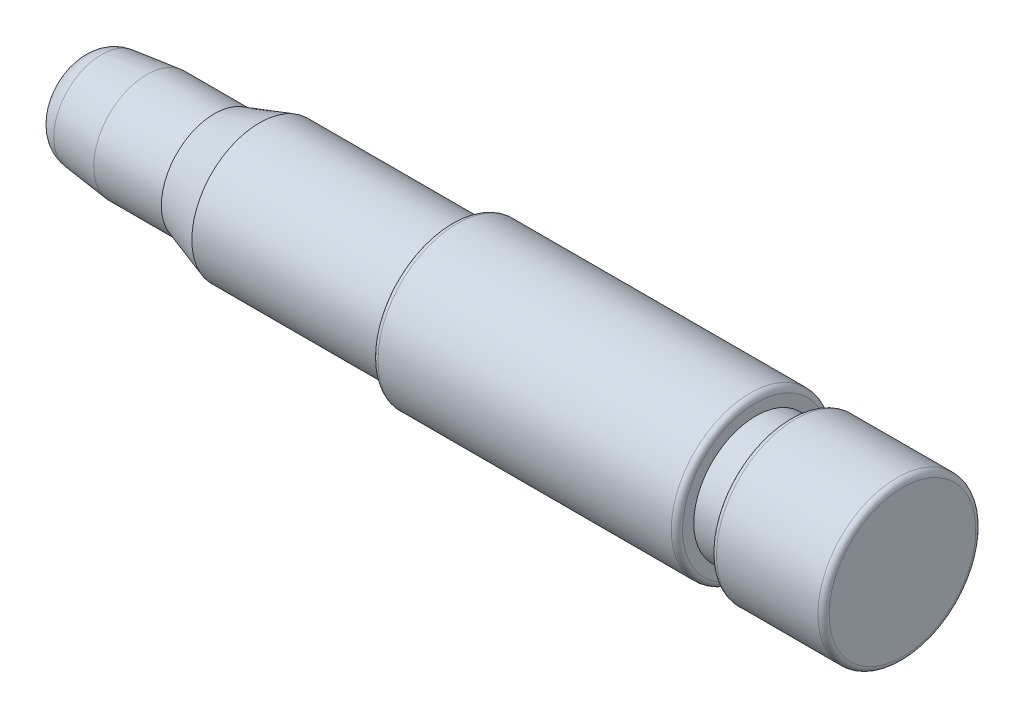
SolidWorks part; units mm, degrees
ref_plane "Plano frontal" through (0, 0, 0) normal (0, 0, 1) x (1, 0, 0)
ref_plane "Plano superior" through (0, 0, 0) normal (0, 1, 0) x (1, 0, 0)
ref_plane "Plano direito" through (0, 0, 0) normal (1, 0, 0) x (0, 0, -1)
sketch "Esboço1" plane through (0, 0, 0) normal (0, 0, 1) x (1, 0, 0)
  line L0 (0, 0) -> (73, 0)
  line L1 (73, 0) -> (73, 7)
  line L2 (73, 7) -> (63, 7)
  line L3 (63, 7) -> (63, 5.5)
  line L4 (63, 5.5) -> (60, 5.5)
  line L5 (60, 5.5) -> (60, 7)
  line L6 (60, 7) -> (33, 7)
  line L7 (33, 7) -> (33, 6)
  line L8 (33, 6) -> (16, 6)
  line L10 (12, 4.7) -> (6, 4.7)
  line L11 (6, 4.7) -> (0, 4)
  line L12 (0, 4) -> (0, 0)
  line L13 (16, 6) -> (12, 4.7)
  dimension "D1" = 4
  dimension "D2" = 4.7
  dimension "D3" = 6
  dimension "D4" = 6
  dimension "D5" = 6
  dimension "D6" = 4
  dimension "D7" = 17
  dimension "D8" = 27
  dimension "D9" = 3
  dimension "D10" = 10
  dimension "D11" = 7
  dimension "D12" = 1.5
  dimension "D13" = 7
  dimension "D14" = 73
revolve "Revolução1" add sketch "Esboço1" angle 360 about L0
cosmetic thread "Representação de rosca1" parameters "D1"=27, "D2"=11.797
cosmetic thread "Representação de rosca2" parameters "D1"=27, "D2"=11.797
sketch "Esboço2" plane through (0, 0, 0) normal (-1, 0, 0) x (0, 0, 1)
  circle A0 centre (0, 0) radius 1.5
  dimension "D1" = 3
extrude "Corte-extrusão1" cut sketch "Esboço2" against normal blind 3
fillet "Filete1" radius 2.25 1 edges at (0, 0, 4)
fillet "Filete2" radius 0.5 4 edges at (33, 0, 7) (60, 0, 7) (63, 0, 7) (73, 0, 7)
